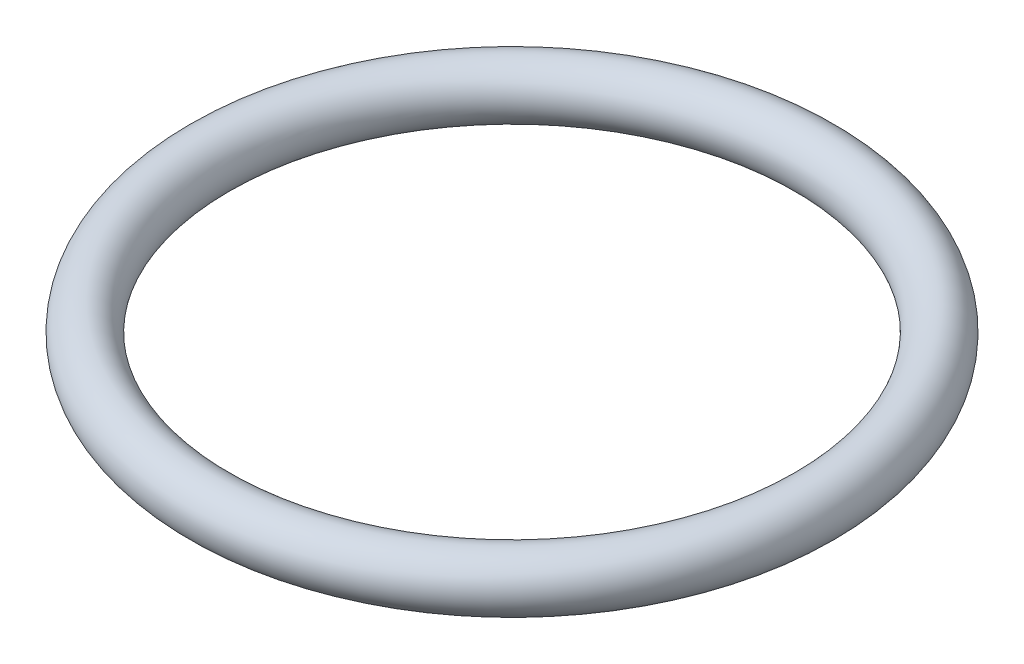
SolidWorks part; units mm, degrees
ref_plane "前视基准面" through (0, 0, 0) normal (0, 0, 1) x (1, 0, 0)
ref_plane "上视基准面" through (0, 0, 0) normal (0, 1, 0) x (1, 0, 0)
ref_plane "右视基准面" through (0, 0, 0) normal (1, 0, 0) x (0, 0, -1)
sketch "草图2" plane through (0, 0, 0) normal (0, 0, 1) x (1, 0, 0)
  circle A0 centre (0, 0) radius 10
  dimension "D1" = 20
sketch "草图4" plane through (0, 0, 0) normal (0, 1, 0) x (1, 0, 0)
  circle A0 centre (-110, 0) radius 110
  dimension "D1" = 220
sweep "扫描1" add profiles "草图2" path "草图4"
sketch "草图5" plane through (0, 0, 0) normal (0, 1, 0) x (1, 0, 0)
  line L0 (-243.6693, 0) -> (76.7536, 0)
